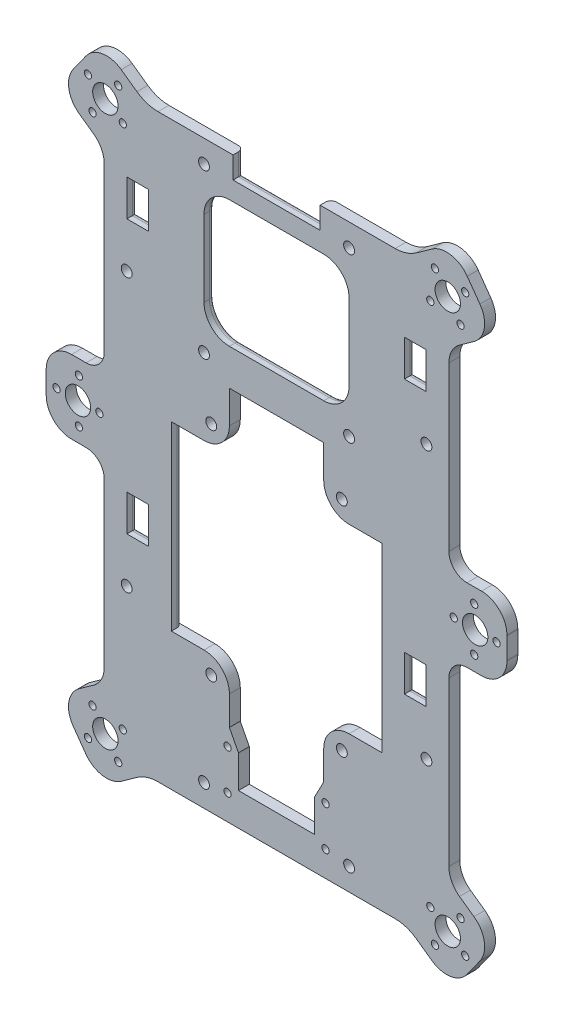
SolidWorks part; units mm, degrees
ref_plane "Front Plane" through (0, 0, 0) normal (0, 0, 1) x (1, 0, 0)
ref_plane "Top Plane" through (0, 0, 0) normal (0, 1, 0) x (1, 0, 0)
ref_plane "Right Plane" through (0, 0, 0) normal (1, 0, 0) x (0, 0, -1)
sketch "Sketch1" plane through (0, 0, 0) normal (0, 0, 1) x (1, 0, 0)
  line L0 (31.9975, -110.362) -> (31.9975, -120.362) construction
  line L1 (-24.4982, 18.6863) -> (-28.8129, 21.7633)
  line L2 (-42.0602, 15.2434) -> (-38.5765, 20.1284)
  line L3 (-36.4405, 2.638) -> (-40.4254, 5.4798)
  line L4 (-33.5049, -3.0612) -> (-33.5049, -48.0612)
  line L5 (-42.5049, -53.0612) -> (-38.5049, -53.0612)
  line L6 (43, -55.362) -> (43, -105.362)
  line L7 (-49.5003, -60.2356) -> (-49.5003, -66.1084)
  line L8 (-49.5049, -60.0612) -> (-49.5003, -60.2356)
  line L9 (46.6871, 16.828) -> (25.9975, 16.828)
  line L10 (77.5, -60.0612) -> (77.4954, -60.2356)
  line L11 (77.4954, -60.2356) -> (77.4954, -66.1084)
  line L12 (70.5, -53.0612) -> (66.5, -53.0612)
  line L13 (61.5, -3.0612) -> (61.5, -48.0612)
  line L14 (64.4356, 2.638) -> (68.4204, 5.4798)
  line L15 (70.0553, 15.2434) -> (66.5716, 20.1284)
  line L16 (52.4933, 18.6863) -> (56.808, 21.7633)
  line L17 (-15.0049, -55.362) -> (-15.0049, -105.362)
  line L18 (52.4933, -145.0303) -> (56.808, -148.1073)
  line L19 (70.0553, -141.5874) -> (66.5716, -146.4724)
  line L20 (64.4356, -128.9821) -> (68.4204, -131.8238)
  line L21 (61.5, -123.2828) -> (61.5, -78.2828)
  line L22 (70.5, -73.2828) -> (66.5, -73.2828)
  line L23 (77.5, -66.2828) -> (77.4954, -66.1084)
  line L24 (46.6871, -143.172) -> (-18.692, -143.172)
  line L25 (-49.5049, -66.2828) -> (-49.5003, -66.1084)
  line L26 (-42.5049, -73.2828) -> (-38.5049, -73.2828)
  line L27 (-33.5049, -123.2828) -> (-33.5049, -78.2828)
  line L28 (-36.4405, -128.9821) -> (-40.4254, -131.8238)
  line L29 (-42.0602, -141.5874) -> (-38.5765, -146.4724)
  line L30 (-24.4982, -145.0303) -> (-28.8129, -148.1073)
  line L31 (13.9975, -143.172) -> (13.9975, -125.172) construction
  line L32 (25.9975, 16.828) -> (1.9975, 16.828) construction
  line L33 (33.9975, -34.362) -> (28.9975, -34.362) construction
  line L34 (28.9975, -34.362) -> (28.9975, -29.362) construction
  line L35 (-6.0025, 10.638) -> (-6.0025, -34.362) construction
  line L36 (33.9975, -34.362) -> (33.9975, -39.362) construction
  line L37 (33.9975, 10.638) -> (33.9975, -34.362) construction
  line L38 (25.9975, 16.828) -> (25.9975, 10.828)
  line L39 (26.9975, -39.362) -> (0.9975, -39.362)
  line L40 (25.9975, 10.828) -> (1.9975, 10.828)
  line L41 (1.9975, 10.828) -> (1.9975, 16.828)
  line L42 (1.9975, 16.828) -> (-18.692, 16.828)
  line L43 (-6.0025, -34.362) -> (-6.0025, -50.362) construction
  line L44 (-6.0025, -50.362) -> (33.9975, -50.362) construction
  line L45 (33.9975, -50.362) -> (33.9975, -34.362) construction
  line L46 (31.9975, -50.362) -> (-4.0025, -50.362) construction
  line L47 (43, -55.362) -> (33.9975, -55.362)
  line L48 (26.9975, -48.362) -> (26.9975, -39.362)
  line L49 (-15.0049, -55.362) -> (-6.0025, -55.362)
  line L50 (0.9975, -48.362) -> (0.9975, -39.362)
  line L51 (31.9975, -110.362) -> (-4.0025, -110.362) construction
  line L52 (33.9975, -105.362) -> (43, -105.362)
  line L53 (31.9975, -120.362) -> (-4.0025, -120.362) construction
  line L54 (-6.0025, -34.362) -> (-1.0025, -34.362) construction
  line L55 (-4.0025, -120.362) -> (-4.0025, -110.362) construction
  line L56 (-1.0025, -34.362) -> (-1.0025, -29.362) construction
  line L57 (33.9975, 10.638) -> (28.9975, 10.638) construction
  line L58 (-6.0025, -105.362) -> (-15.0049, -105.362)
  line L59 (28.9975, 10.638) -> (28.9975, 5.638) construction
  line L60 (-6.0025, 10.638) -> (-1.0025, 10.638) construction
  line L61 (-1.0025, 10.638) -> (-1.0025, 5.638) construction
  line L62 (33.9975, -1.362) -> (33.9975, -22.362)
  line L63 (26.9975, -29.362) -> (0.9975, -29.362)
  line L64 (-6.0025, -22.362) -> (-6.0025, -1.362)
  line L65 (0.9975, 5.638) -> (26.9975, 5.638)
  line L66 (27.4975, -143.172) -> (0.4975, -143.172) construction
  line L67 (0.4975, -143.172) -> (0.4975, -136.172) construction
  line L68 (0.4975, -136.172) -> (27.4975, -136.172) construction
  line L69 (0.4975, -136.172) -> (0.4975, -125.172) construction
  line L70 (0.4975, -125.172) -> (27.4975, -125.172) construction
  line L71 (27.4975, -125.172) -> (27.4975, -136.172) construction
  line L72 (26.9975, -112.362) -> (26.9975, -120.362)
  line L73 (61.5, -78.2828) -> (43, -78.2828) construction
  line L74 (0.9975, -120.362) -> (0.9975, -112.362)
  line L75 (0.4975, -143.172) -> (0.4975, -113.172) construction
  line L76 (0.4975, -113.172) -> (27.4975, -113.172) construction
  line L77 (27.4975, -125.172) -> (24.4975, -125.172) construction
  line L78 (24.4975, -125.172) -> (24.4975, -134.172) construction
  line L79 (24.4975, -134.172) -> (3.4975, -134.172) construction
  line L80 (3.4975, -134.172) -> (3.4975, -125.172) construction
  line L81 (24.4975, -125.172) -> (24.4975, -134.172)
  line L82 (24.4975, -134.172) -> (3.4975, -134.172)
  line L83 (3.4975, -134.172) -> (3.4975, -125.172)
  line L84 (3.4975, -125.172) -> (0.9975, -120.362)
  line L85 (26.9975, -120.362) -> (24.4975, -125.172)
  line L86 (55.25, -78.2828) -> (49.25, -78.2828)
  line L87 (49.25, -78.2828) -> (49.25, -88.2828)
  line L88 (49.25, -88.2828) -> (55.25, -88.2828)
  line L89 (55.25, -88.2828) -> (55.25, -78.2828)
  line L90 (-15.0049, -78.2828) -> (-33.5049, -78.2828) construction
  line L91 (-21.2549, -78.2828) -> (-27.2549, -78.2828)
  line L92 (-27.2549, -78.2828) -> (-27.2549, -88.2828)
  line L93 (-27.2549, -88.2828) -> (-21.2549, -88.2828)
  line L94 (-21.2549, -88.2828) -> (-21.2549, -78.2828)
  line L95 (61.5, -3.0612) -> (43, -3.0612) construction
  line L96 (43, -3.0612) -> (43, -55.362) construction
  line L97 (55.25, -3.0612) -> (49.25, -3.0612)
  line L98 (49.25, -3.0612) -> (49.25, -13.0612)
  line L99 (49.25, -13.0612) -> (55.25, -13.0612)
  line L100 (55.25, -13.0612) -> (55.25, -3.0612)
  line L101 (-33.5049, -3.0612) -> (-15.0049, -3.0612) construction
  line L102 (-15.0049, -3.0612) -> (-15.0049, -55.362) construction
  line L103 (-21.2549, -3.0612) -> (-27.2549, -3.0612)
  line L104 (-27.2549, -3.0612) -> (-27.2549, -13.0612)
  line L105 (-27.2549, -13.0612) -> (-21.2549, -13.0612)
  line L106 (-21.2549, -13.0612) -> (-21.2549, -3.0612)
  circle A0 centre (-37.998, 16.0311) radius 1
  circle A1 centre (-29.6584, 17.5638) radius 1
  circle A2 centre (-36.7303, 7.6471) radius 1
  arc A3 (-38.5049, -53.0612) -> (-33.5049, -48.0612) centre (-38.5049, -48.0612) ccw
  arc A4 (-49.5049, -60.0612) -> (-42.5049, -53.0612) centre (-42.5049, -60.0612) cw
  circle A5 centre (-28.3907, 9.1798) radius 1
  circle A6 centre (-33.1943, 12.6054) radius 3.5
  arc A7 (-24.4982, 18.6863) -> (-18.692, 16.828) centre (-18.692, 26.828) ccw
  arc A8 (-40.4254, 5.4798) -> (-42.0602, 15.2434) centre (-36.361, 11.179) cw
  arc A9 (-38.5765, 20.1284) -> (-28.8129, 21.7633) centre (-32.8773, 16.0641) cw
  arc A10 (-33.5049, -3.0612) -> (-36.4405, 2.638) centre (-40.5049, -3.0612) ccw
  arc A11 (61.5, -3.0612) -> (64.4356, 2.638) centre (68.5, -3.0612) cw
  arc A12 (66.5716, 20.1284) -> (56.808, 21.7633) centre (60.8724, 16.0641) ccw
  arc A13 (68.4204, 5.4798) -> (70.0553, 15.2434) centre (64.3561, 11.179) ccw
  arc A14 (52.4933, 18.6863) -> (46.6871, 16.828) centre (46.6871, 26.828) cw
  circle A15 centre (61.1894, 12.6054) radius 3.5
  circle A16 centre (56.3858, 9.1798) radius 1
  arc A17 (77.5, -60.0612) -> (70.5, -53.0612) centre (70.5, -60.0612) ccw
  arc A18 (66.5, -53.0612) -> (61.5, -48.0612) centre (66.5, -48.0612) cw
  circle A19 centre (64.7254, 7.6471) radius 1
  circle A20 centre (57.6534, 17.5638) radius 1
  circle A21 centre (65.9931, 16.0311) radius 1
  circle A22 centre (65.9931, -142.3751) radius 1
  circle A23 centre (57.6534, -143.9078) radius 1
  circle A24 centre (64.7254, -133.9911) radius 1
  arc A25 (66.5, -73.2828) -> (61.5, -78.2828) centre (66.5, -78.2828) ccw
  arc A26 (77.5, -66.2828) -> (70.5, -73.2828) centre (70.5, -66.2828) cw
  circle A27 centre (56.3858, -135.5238) radius 1
  circle A28 centre (61.1894, -138.9495) radius 3.5
  arc A29 (52.4933, -145.0303) -> (46.6871, -143.172) centre (46.6871, -153.172) ccw
  arc A30 (68.4204, -131.8238) -> (70.0553, -141.5874) centre (64.3561, -137.523) cw
  arc A31 (66.5716, -146.4724) -> (56.808, -148.1073) centre (60.8724, -142.4081) cw
  arc A32 (61.5, -123.2828) -> (64.4356, -128.9821) centre (68.5, -123.2828) ccw
  arc A33 (-33.5049, -123.2828) -> (-36.4405, -128.9821) centre (-40.5049, -123.2828) cw
  arc A34 (-38.5765, -146.4724) -> (-28.8129, -148.1073) centre (-32.8773, -142.4081) ccw
  arc A35 (-40.4254, -131.8238) -> (-42.0602, -141.5874) centre (-36.361, -137.523) ccw
  arc A36 (-24.4982, -145.0303) -> (-18.692, -143.172) centre (-18.692, -153.172) cw
  circle A37 centre (-33.1943, -138.9495) radius 3.5
  circle A38 centre (-28.3907, -135.5238) radius 1
  arc A39 (-49.5049, -66.2828) -> (-42.5049, -73.2828) centre (-42.5049, -66.2828) ccw
  arc A40 (-38.5049, -73.2828) -> (-33.5049, -78.2828) centre (-38.5049, -78.2828) cw
  circle A41 centre (-36.7303, -133.9911) radius 1
  circle A42 centre (-29.6584, -143.9078) radius 1
  circle A43 centre (-37.998, -142.3751) radius 1
  circle A44 centre (-6.0025, -34.362) radius 1.5
  circle A45 centre (55.31, -25.5612) radius 1.5
  circle A46 centre (33.9975, -136.982) radius 1.5
  circle A47 centre (-6.0025, -136.982) radius 1.5
  circle A48 centre (-6.0025, 10.638) radius 1.5
  circle A49 centre (33.9975, 10.638) radius 1.5
  circle A50 centre (33.9975, -34.362) radius 1.5
  circle A51 centre (31.9975, -50.362) radius 1.5
  circle A52 centre (-4.0025, -50.362) radius 1.5
  arc A53 (-6.0025, -55.362) -> (0.9975, -48.362) centre (-6.0025, -48.362) ccw
  arc A54 (33.9975, -55.362) -> (26.9975, -48.362) centre (33.9975, -48.362) cw
  circle A55 centre (-4.0025, -110.362) radius 1.5
  circle A56 centre (31.9975, -110.362) radius 1.5
  arc A57 (0.9975, -112.362) -> (-6.0025, -105.362) centre (-6.0025, -112.362) ccw
  arc A58 (33.9975, -105.362) -> (26.9975, -112.362) centre (33.9975, -112.362) ccw
  arc A59 (33.9975, -22.362) -> (26.9975, -29.362) centre (26.9975, -22.362) cw
  circle A60 centre (-27.3149, -25.5612) radius 1.5
  circle A61 centre (55.31, -100.7828) radius 1.5
  circle A62 centre (-27.3149, -100.7828) radius 1.5
  arc A63 (0.9975, -29.362) -> (-6.0025, -22.362) centre (0.9975, -22.362) cw
  arc A64 (-6.0025, -1.362) -> (0.9975, 5.638) centre (0.9975, -1.362) cw
  arc A65 (33.9975, -1.362) -> (26.9975, 5.638) centre (26.9975, -1.362) ccw
  circle A66 centre (27.4975, -136.172) radius 1
  circle A67 centre (0.4975, -136.172) radius 1
  circle A68 centre (27.4975, -125.172) radius 1
  circle A69 centre (0.4975, -125.172) radius 1
  circle A74 centre (-40.7503, -63.172) radius 3.5
  circle A75 centre (-46.6503, -63.172) radius 1
  circle A76 centre (-34.8503, -63.172) radius 1
  circle A77 centre (-40.4873, -69.2563) radius 1
  circle A78 centre (-40.4873, -57.0877) radius 1
  circle A79 centre (68.4824, -57.0877) radius 1
  circle A80 centre (68.4824, -69.2563) radius 1
  circle A81 centre (62.8454, -63.172) radius 1
  circle A82 centre (74.6454, -63.172) radius 1
  circle A83 centre (68.7454, -63.172) radius 3.5
  point P25 (-34.5122, 25.8276)
  point P29 (-34.5122, 25.8276)
  point P64 (62.5072, 25.8276)
  point P95 (62.5072, -152.1716)
  point P124 (-34.5122, -152.1716)
  point P144 (13.9975, 16.828)
  point P147 (13.9975, 16.828)
  point P154 (13.9975, -50.362)
  point P182 (13.9975, -125.172)
  point P196 (33.9975, -29.362)
  point P199 (-6.0025, -29.362)
  point P202 (-6.0025, 5.638)
  point P215 (33.9975, 5.638)
  point P229 (13.9975, -143.172)
  point P249 (52.25, -78.2828)
  point P256 (-24.2549, -78.2828)
  point P261 (52.25, -3.0612)
  point P267 (-24.2549, -3.0612)
  dimension "D6" = 7
  dimension "D7" = 7
  dimension "D1" = 10
  dimension "D2" = 7
  dimension "D3" = 7
  dimension "D4" = 5
  dimension "D5" = 7
  dimension "D8" = 7
extrude "Бобышка-Вытянуть1" add sketch "Sketch1" against normal blind 3
fillet "Скругление1" radius 1.5 16 edges at (52.25, -88.2828, -3) (55.25, -83.2828, -3) (49.25, -83.2828, -3) (52.25, -78.2828, -3) (-24.2549, -88.2828, -3) (-27.2549, -83.2828, -3) (-21.2549, -83.2828, -3) (-24.2549, -78.2828, -3) (-27.2549, -8.0612, -3) (-21.2549, -8.0612, -3) (-24.2549, -13.0612, -3) (-24.2549, -3.0612, -3) (52.25, -13.0612, -3) (52.25, -3.0612, -3) (49.25, -8.0612, -3) (55.25, -8.0612, -3)
fillet "Скругление2" radius 1.5 14 edges at (31.9473, 3.5877, -3) (33.9975, -11.862, -3) (31.9473, -27.3118, -3) (13.9975, -29.362, -3) (-3.9522, -27.3118, -3) (-6.0025, -11.862, -3) (-3.9522, 3.5877, -3) (13.9975, 5.638, -3) (43, -80.362, -3) (-15.0049, -80.362, -3) (13.9975, -39.362, -3) (25.9975, 13.828, -3) (1.9975, 13.828, -3) (13.9975, 10.828, -3)
sketch "Эскиз1" plane through (0, 0, -3) normal (0, 0, -1) x (-1, 0, 0)
  line L0 (22.001, -14.5612) -> (22.001, -55.868) construction
  text T0 "AGILE" font "Century Gothic" height in points 36
  point P3 (20.41, -14.5612)
  point P5 (24.2549, -53.3878)
  point P6 (24.2549, -14.5612)
  point P7 (0, 0)
  point P9 (0, 0)
  point P10 (0, 0)
  point P11 (0, 0)
  point P12 (0, 0)
extrude "Вырез-Вытянуть1" cut sketch "Эскиз1" against normal blind 2.6
